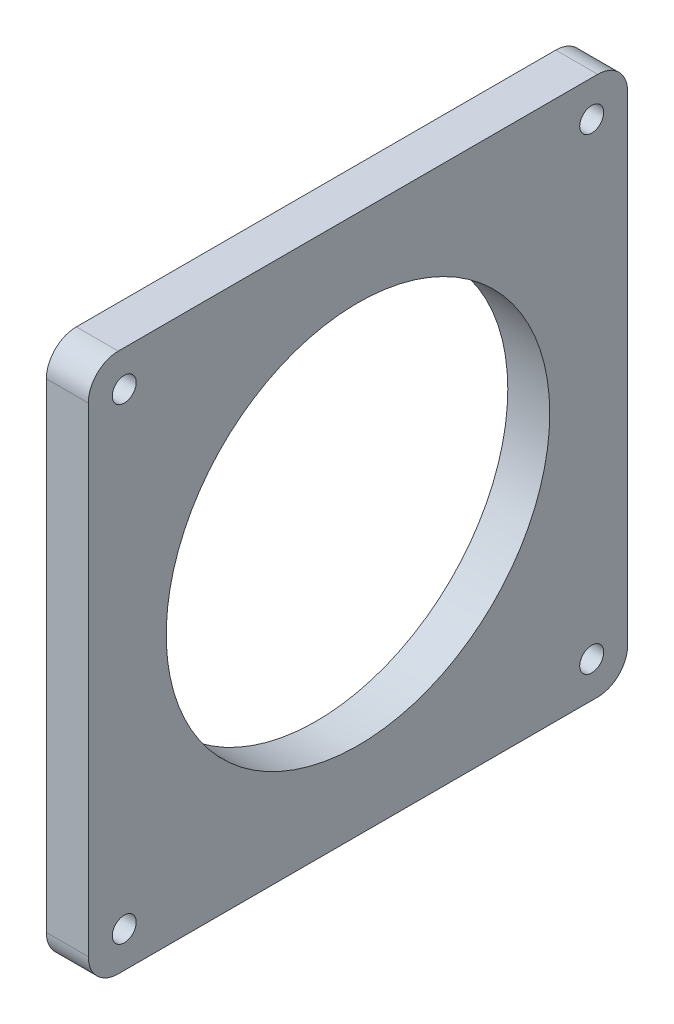
SolidWorks part; units mm, degrees
ref_plane "Plan de face" through (0, 0, 0) normal (0, 0, 1) x (1, 0, 0)
ref_plane "Plan de dessus" through (0, 0, 0) normal (0, 1, 0) x (1, 0, 0)
ref_plane "Plan de droite" through (0, 0, 0) normal (1, 0, 0) x (0, 0, -1)
sketch "Esquisse1" plane through (0, 0, 0) normal (1, 0, 0) x (0, 0, -1)
  circle A0 centre (0, 0) radius 32
  circle A1 centre (0, 0) radius 45
  dimension "D1" = 64
  dimension "D2" = 90
extrude "Boss.-Extru.1" add sketch "Esquisse1" along normal blind 7
sketch "Esquisse3" plane through (7, 0, 0) normal (1, 0, 0) x (0, 0, -1)
  line L0 (0, 0) -> (0, 54.6476) construction
  line L1 (0, 0) -> (-32.909, 19) construction
  line L2 (-20.8487, 32.3664) -> (-17.3288, 26.9019) construction
  line L3 (-20.8487, 32.3664) -> (-24.3686, 37.8308) construction
  circle A0 centre (0, 38) radius 2.5
  circle A1 centre (32.909, 19) radius 2.5
  circle A2 centre (32.909, -19) radius 2.5
  circle A3 centre (0, -38) radius 2.5
  circle A4 centre (-32.909, -19) radius 2.5
  circle A5 centre (-32.909, 19) radius 2.5
  circle A6 centre (-20.8487, 32.3664) radius 4
  circle A7 centre (0, 0) radius 32 construction
  circle A8 centre (0, 0) radius 45 construction
  circle A9 centre (38.4544, 1.8723) radius 4
  circle A10 centre (-17.6057, -34.2387) radius 4
  dimension "D1" = 5
  dimension "D5" = 8
  dimension "D3" = 38
  dimension "D4" = 3
  dimension "D2" = 6
extrude "Enlèv. mat.-Extru.1" cut sketch "Esquisse3" against normal through all
sketch "Esquisse4" plane through (7, 0, 0) normal (1, 0, 0) x (0, 0, -1)
  line L1 (-45, -45) -> (45, -45)
  line L2 (-45, -45) -> (-45, 45)
  line L3 (-45, 45) -> (45, 45)
  line L4 (45, -45) -> (45, 45)
  line L5 (-45, -45) -> (45, 45) construction
  line L6 (-45, 45) -> (45, -45) construction
  circle A0 centre (0, 0) radius 45 construction
  circle A1 centre (0, 0) radius 32 construction
  circle A2 centre (0, 0) radius 32
  point P0 (0, 0)
  circle M15 centre (0, 0) radius 45
extrude "Boss.-Extru.3" add sketch "Esquisse4" against normal up to surface (7 mm away) contours L2 L1 M15 | L4 L3 M15 | L1 L4 M15 | L3 L2 M15 | A2
sketch "Esquisse5" plane through (0, 0, 0) normal (-1, 0, 0) x (0, 0, 1)
  line L0 (-45, 45) -> (-45, -45) construction
  line L1 (-45, 45) -> (45, 45) construction
  line L2 (0, 0) -> (0, 75.3686) construction
  line L3 (0, 0) -> (69.5067, 0) construction
  circle A0 centre (-39, 39) radius 2
  circle A1 centre (39, 39) radius 2
  circle A2 centre (39, -39) radius 2
  circle A3 centre (-39, -39) radius 2
  dimension "D1" = 4
  dimension "D2" = 6
  dimension "D3" = 6
extrude "Enlèv. mat.-Extru.2" cut sketch "Esquisse5" against normal through all
fillet "Congé1" radius 5 4 edges at (3.5, -45, 45) (3.5, -45, -45) (3.5, 45, -45) (3.5, 45, 45)
